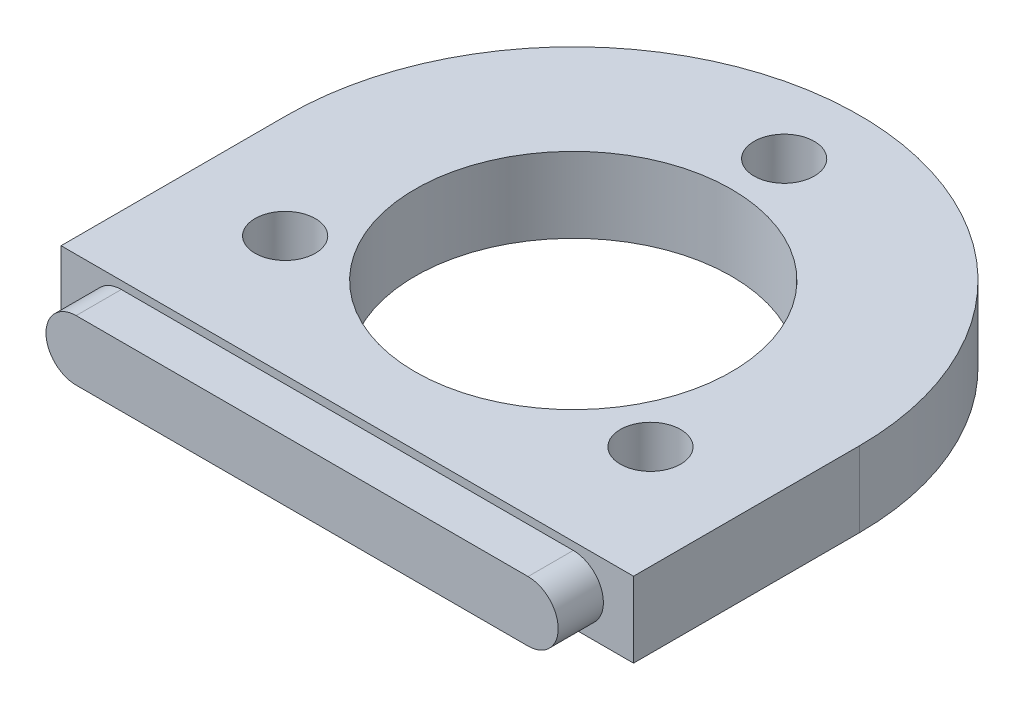
SolidWorks part; units mm, degrees
ref_plane "Front Plane" through (0, 0, 0) normal (0, 0, 1) x (1, 0, 0)
ref_plane "Top Plane" through (0, 0, 0) normal (0, 1, 0) x (1, 0, 0)
ref_plane "Right Plane" through (0, 0, 0) normal (1, 0, 0) x (0, 0, -1)
sketch "Sketch1" plane through (0, 0, 0) normal (0, 1, 0) x (1, 0, 0)
  line L0 (-44.2539, 0) -> (44.2539, 0) construction
  line L1 (19, 0) -> (19, -15)
  line L2 (19, -15) -> (-19, -15)
  line L3 (-19, -15) -> (-19, 0)
  arc A0 (-19, 0) -> (19, 0) centre (0, 0) cw
  dimension "D1" = 19
  dimension "D2" = 15
extrude "Boss-Extrude1" add sketch "Sketch1" along normal blind 5
sketch "Sketch2" plane through (0, 0, 15) normal (0, 0, 1) x (1, 0, 0)
  line L0 (-15, 2.482) -> (15, 2.482) construction
  line L1 (0, -44.7868) -> (0, 44.7868) construction
  line L2 (-15, 4.482) -> (15, 4.482)
  line L3 (-15, 0.482) -> (15, 0.482)
  arc A0 (-15, 4.482) -> (-15, 0.482) centre (-15, 2.482) ccw
  arc A1 (15, 0.482) -> (15, 4.482) centre (15, 2.482) ccw
  point P4 (0, 2.482)
  dimension "D2" = 2
  dimension "D1" = 30
extrude "Boss-Extrude2" add sketch "Sketch2" along normal blind 3
sketch "Sketch3" plane through (0, 5, 0) normal (0, 1, 0) x (1, 0, 0)
  circle A0 centre (0, 0) radius 10.5
  dimension "D1" = 21
extrude "Cut-Extrude1" cut sketch "Sketch3" against normal blind 5
sketch "Sketch4" plane through (0, 5, 0) normal (0, 1, 0) x (1, 0, 0)
  line L0 (0, -44.7868) -> (0, 44.7868) construction
  circle A0 centre (0, 14) radius 2
  circle A1 centre (0, 0) radius 10.5 construction
  dimension "D1" = 14
extrude "Cut-Extrude2" cut sketch "Sketch4" against normal blind 10
pattern_circular "CirPattern1" count 3 over 360 about axis through (0, 0, 0) along (0, 1, 0) of "Cut-Extrude2"
